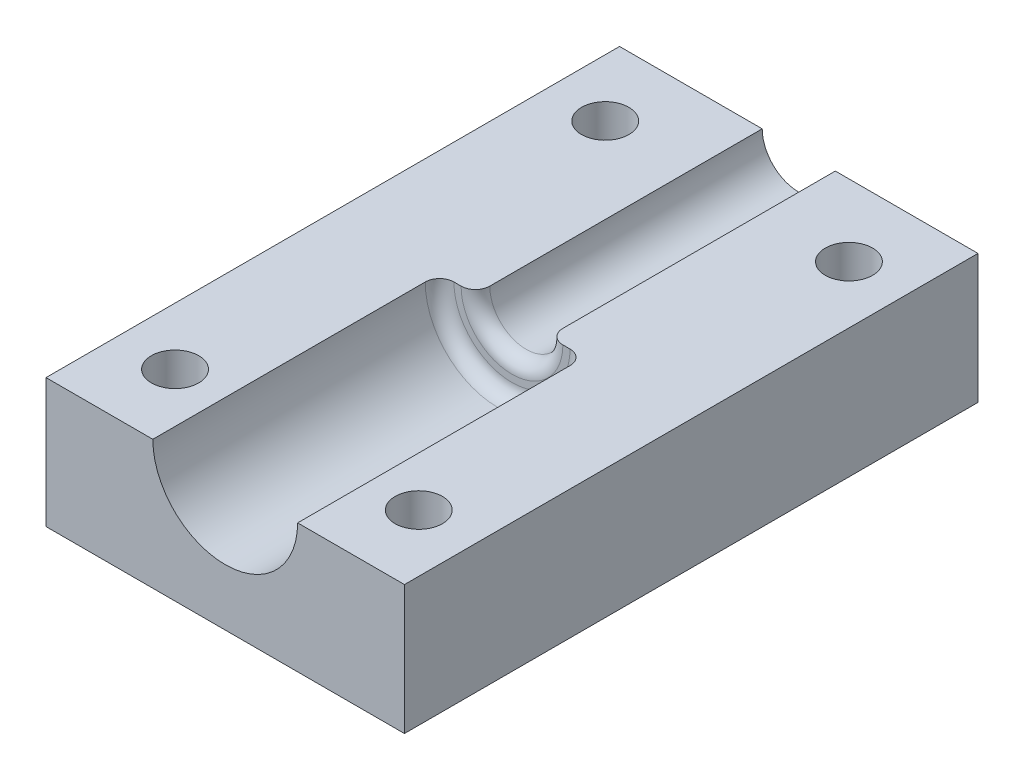
SolidWorks part; units mm, degrees
ref_plane "Ebene vorne" through (0, 0, 0) normal (0, 0, 1) x (1, 0, 0)
ref_plane "Ebene oben" through (0, 0, 0) normal (0, 1, 0) x (1, 0, 0)
ref_plane "Ebene rechts" through (0, 0, 0) normal (1, 0, 0) x (0, 0, -1)
sketch "Skizze1" plane through (0, 0, 0) normal (0, 1, 0) x (1, 0, 0)
  line L0 (0, 0) -> (25, 0)
  line L1 (25, 0) -> (25, 40)
  line L2 (25, 40) -> (0, 40)
  line L3 (0, 40) -> (0, 0)
  line L4 (12.5, 0) -> (12.5, 40)
  line L5 (0, 20) -> (25, 20)
  line L6 (0, 0) -> (0, 5)
  line L7 (0, 5) -> (4, 5)
  circle A0 centre (4, 5) radius 1.65
  circle A1 centre (21, 5) radius 1.65
  circle A2 centre (21, 35) radius 1.65
  circle A3 centre (4, 35) radius 1.65
  dimension "D3" = 3.3
  dimension "D1" = 25
  dimension "D2" = 40
  dimension "D4" = 5
  dimension "D5" = 4
extrude "Aufsatz-Linear austragen1" add sketch "Skizze1" along normal blind 9
sketch "Skizze2" plane through (0, 0, 0) normal (0, 0, 1) x (1, 0, 0)
  line L0 (0, 9) -> (25, 9) construction
  line L1 (17.55, 9) -> (7.45, 9)
  arc A0 (17.55, 9) -> (7.45, 9) centre (12.5, 9) cw
  dimension "D1" = 5.05
sketch "Skizze3" plane through (0, 0, -40) normal (0, 0, -1) x (-1, 0, 0)
  line L0 (-25, 9) -> (0, 9) construction
  line L1 (-15.05, 9) -> (-9.95, 9)
  arc A0 (-9.95, 9) -> (-15.05, 9) centre (-12.5, 9) cw
  dimension "D1" = 2.55
extrude "Schnitt-Linear austragen2" cut sketch "Skizze3" against normal blind 20
extrude "Schnitt-Linear austragen3" cut sketch "Skizze2" against normal blind 20 contours A0 L1
fillet "Verrundung1" radius 1 2 edges at (12.5, 3.95, -20) (12.5, 6.45, -20)
equation "\"M4_mutter\"= 7.4mm"
equation "\"M4_loch\"= 4.3mm"
equation "\"M8_loch\"= 8.4mm"
equation "\"D3@Skizze1\"=\"M3_loch\""
equation "\"M3_loch\"= 3.3mm"
